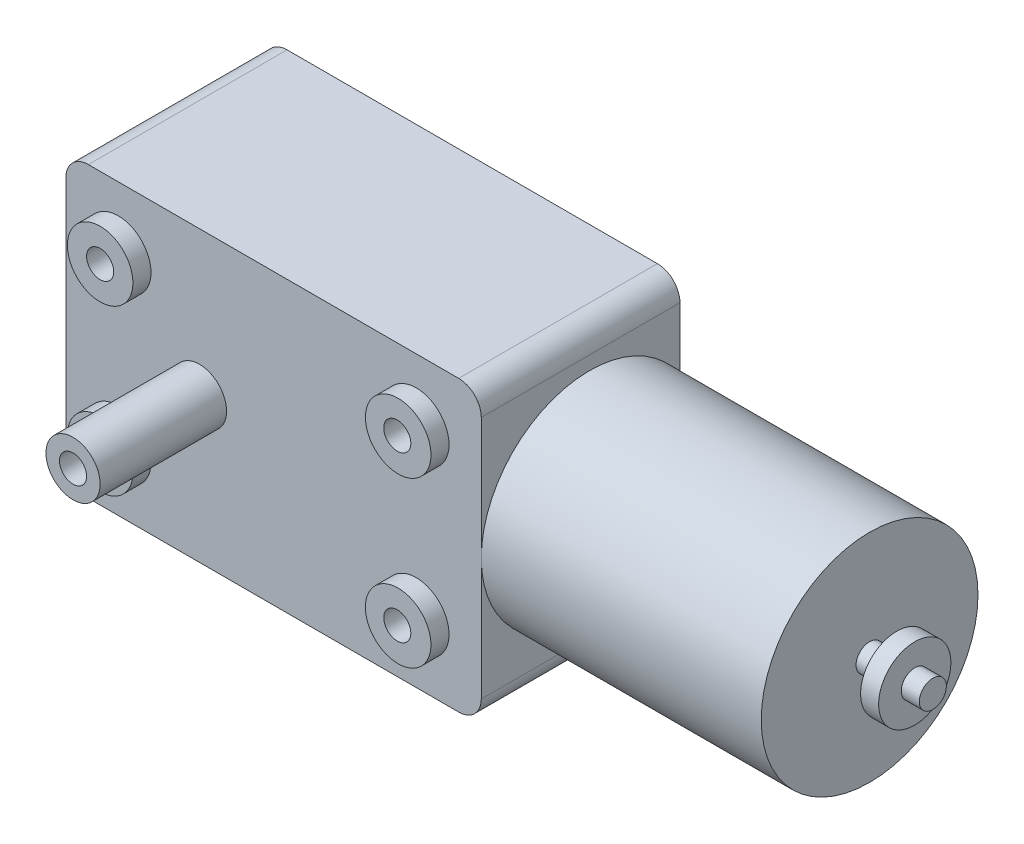
SolidWorks part; units mm, degrees
ref_plane "Front Plane" through (0, 0, 0) normal (0, 0, 1) x (1, 0, 0)
ref_plane "Top Plane" through (0, 0, 0) normal (0, 1, 0) x (1, 0, 0)
ref_plane "Right Plane" through (0, 0, 0) normal (1, 0, 0) x (0, 0, -1)
sketch "Sketch1" plane through (0, 0, 0) normal (0, 0, 1) x (1, 0, 0)
  line L0 (-23, 0) -> (23, 0) construction
  line L1 (-20.5, -16) -> (20.5, -16)
  line L2 (-23, -13.5) -> (-23, 13.5)
  line L3 (-20.5, 16) -> (20.5, 16)
  line L4 (23, -13.5) -> (23, 13.5)
  line L5 (-23, -16) -> (23, 16) construction
  line L6 (-23, 16) -> (23, -16) construction
  line L7 (0, 16) -> (0, -16) construction
  arc A0 (23, 13.5) -> (20.5, 16) centre (20.5, 13.5) ccw
  arc A1 (23, -13.5) -> (20.5, -16) centre (20.5, -13.5) cw
  arc A2 (-20.5, -16) -> (-23, -13.5) centre (-20.5, -13.5) cw
  arc A3 (-23, 13.5) -> (-20.5, 16) centre (-20.5, 13.5) cw
  point P0 (0, 0)
  dimension "D3" = 2.5
  dimension "D1" = 32
  dimension "D2" = 46
extrude "Boss-Extrude1" add sketch "Sketch1" along normal blind 22 contours A3 L2 A2 L1 A1 L4 A0 L3
sketch "Sketch2" plane through (0, 0, 22) normal (0, 0, 1) x (1, 0, 0)
  line L0 (-23, 0) -> (23, 0) construction
  line L1 (-23, -13.5) -> (-23, 13.5) construction
  line L2 (23, -13.5) -> (23, 13.5) construction
  circle A0 centre (-8.2, 0) radius 3
  dimension "D1" = 6
  dimension "D2" = 14.8
extrude "Boss-Extrude2" add sketch "Sketch2" along normal blind 14 contours A0
sketch "Sketch5" plane through (0, 0, 22) normal (0, 0, 1) x (1, 0, 0)
  line L0 (-23, 0) -> (23, 0) construction
  line L1 (-23, -13.5) -> (-23, 13.5) construction
  line L2 (23, -13.5) -> (23, 13.5) construction
  line L3 (-8.2, 0) -> (-8.2, 16) construction
  line L4 (-20.5, 16) -> (20.5, 16) construction
  line L5 (-17.2, -16) -> (-17.2, 16) construction
  line L6 (-20.5, -16) -> (20.5, -16) construction
  line L7 (0, 0) -> (0, 16) construction
  line L8 (0, 16) -> (0, -16) construction
  circle A0 centre (-17.2, 9.11) radius 3.63
  circle A4 centre (-17.2, -9.09) radius 3.63
  circle A5 centre (15.8, 9.11) radius 3.63
  circle A6 centre (15.8, -9.09) radius 3.63
  dimension "D2" = 7.26
  dimension "D5" = 7.26
  dimension "D8" = 7.26
  dimension "D1" = 9
  dimension "D3" = 2
  dimension "D4" = 18.2
  dimension "D6" = 6.89
  dimension "D10" = 33
  dimension "D7" = 2
extrude "Boss-Extrude3" add sketch "Sketch5" along normal blind 2
sketch "Sketch7" plane through (0, 0, 24) normal (0, 0, 1) x (1, 0, 0)
  circle A0 centre (-17.2, 9.11) radius 1.5
  circle A1 centre (-17.2, 9.11) radius 3.63 construction
  circle A2 centre (-17.2, -9.09) radius 1.5
  circle A3 centre (15.7, 9.11) radius 1.5
  circle A4 centre (15.7, -9.09) radius 1.5
  dimension "D1" = 2
  dimension "D3" = 3
  dimension "D4" = 32.9
  dimension "D5" = 18.2
  dimension "D2" = 2
extrude "Cut-Extrude1" cut sketch "Sketch7" against normal blind 3.5
sketch "Sketch8" plane through (23, 0, 0) normal (1, 0, 0) x (0, 0, -1)
  line L0 (-11, 16) -> (-11, -16) construction
  line L1 (-22, 16) -> (0, 16) construction
  line L2 (-22, -16) -> (0, -16) construction
  line L3 (-22, -13.5) -> (-22, 13.5) construction
  line L5 (-22, 13.5) -> (0, 13.5) construction
  circle A0 centre (-10, 0) radius 12
  dimension "D1" = 24
  dimension "D2" = 13.5
extrude "Boss-Extrude4" add sketch "Sketch8" along normal blind 31 contours A0
sketch "Sketch9" plane through (54, 0, 0) normal (1, 0, 0) x (0, 0, -1)
  circle A0 centre (-10, 0) radius 1.5
  circle A1 centre (-10, 0) radius 12 construction
  dimension "D1" = 3
extrude "Boss-Extrude5" add sketch "Sketch9" along normal blind 7
ref_plane "Plane1" through (57, 0, 0) normal (1, 0, 0) x (0, 0, -1)
sketch "Sketch10" plane through (57, 0, 0) normal (1, 0, 0) x (0, 0, -1)
  circle A0 centre (-10, 0) radius 4
  circle A1 centre (-10, 0) radius 1.5
  dimension "D1" = 3
  dimension "D2" = 8
extrude "Boss-Extrude6" add sketch "Sketch10" along normal blind 2 contours A0
sketch "Sketch11" plane through (0, 0, 36) normal (0, 0, 1) x (1, 0, 0)
  circle A0 centre (-8.2, 0) radius 1.5
  circle A1 centre (-8.2, 0) radius 3 construction
  dimension "D1" = 3
extrude "Cut-Extrude2" cut sketch "Sketch11" against normal blind 3.5
